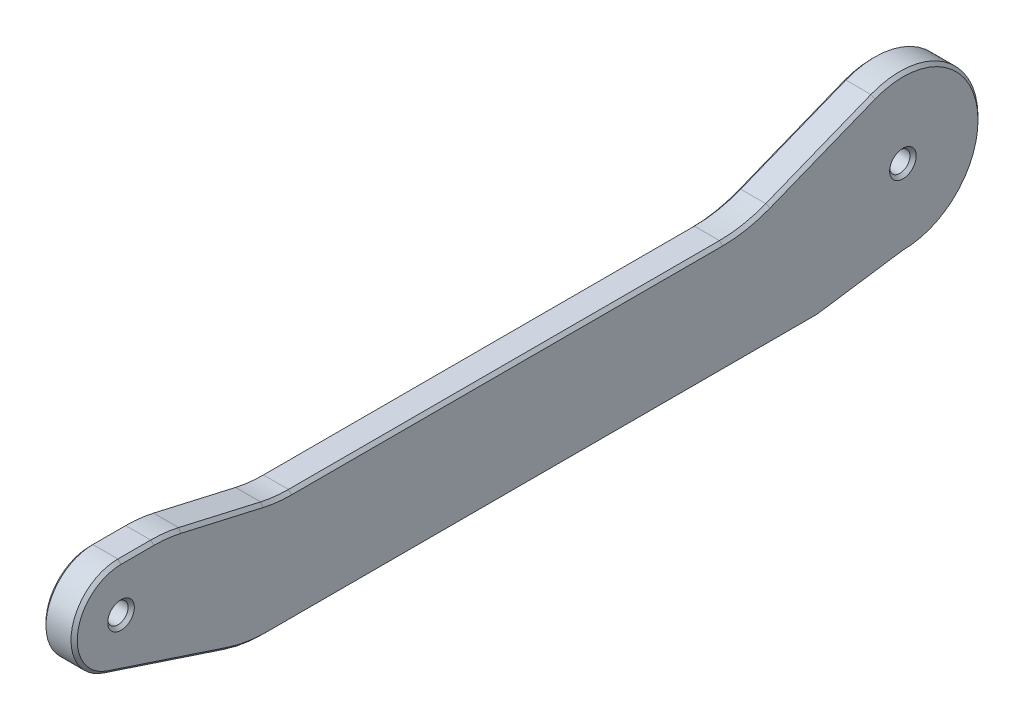
SolidWorks part; units mm, degrees
ref_plane "前视基准面" through (0, 0, 0) normal (0, 0, 1) x (1, 0, 0)
ref_plane "上视基准面" through (0, 0, 0) normal (0, 1, 0) x (1, 0, 0)
ref_plane "右视基准面" through (0, 0, 0) normal (1, 0, 0) x (0, 0, -1)
ref_plane "基准面1" through (2.5, 0, 0) normal (1, 0, 0) x (0, 0, -1)
sketch "草图1" plane through (2.5, 0, 0) normal (1, 0, 0) x (0, 0, -1)
  line L0 (-87.5, -4) -> (-32.5, -4)
  line L1 (-32.5, -7) -> (-87.5, -7)
  line L2 (-28.8354, 3.5) -> (-97.7434, 3.5)
  line L3 (-102.1999, 4.0028) -> (-115.3001, 6.9972)
  line L4 (-119.7566, 7.5) -> (-125, 7.5)
  line L5 (-127.351, -7.122) -> (-108.0536, -13.492)
  line L6 (-101.7844, -14.5) -> (-13.675, -14.5)
  line L7 (-13.675, -14.5) -> (0, -12.5)
  line L8 (-4.6241, 11.6132) -> (-21.4367, 4.9188)
  circle A0 centre (-125, 0) radius 1.625
  circle A1 centre (-97.5, -5.5) radius 1.5
  circle A2 centre (-20, -5.5) radius 1.5
  arc A3 (-87.5, -7) -> (-87.5, -4) centre (-87.5, -5.5) cw
  arc A4 (-32.5, -4) -> (-32.5, -7) centre (-32.5, -5.5) cw
  arc A5 (-97.7434, 3.5) -> (-102.1999, 4.0028) centre (-97.7434, 23.5) cw
  arc A6 (-115.3001, 6.9972) -> (-119.7566, 7.5) centre (-119.7566, -12.5) ccw
  arc A7 (-125, 7.5) -> (-127.351, -7.122) centre (-125, 0) ccw
  arc A8 (-108.0536, -13.492) -> (-101.7844, -14.5) centre (-101.7844, 5.5) ccw
  arc A9 (0, -12.5) -> (-4.6241, 11.6132) centre (0, 0) ccw
  arc A10 (-21.4367, 4.9188) -> (-28.8354, 3.5) centre (-28.8354, 23.5) cw
  circle A11 centre (0, 0) radius 1.625
  dimension "D4" = 1.5
  dimension "D5" = 3
  dimension "D6" = 3.25
  dimension "D7" = 12.5
  dimension "D1" = 3
  dimension "D2" = 68.908
  dimension "D3" = 7.5
  dimension "D8" = 18.0964
extrude "凸台-拉伸1" add sketch "草图1" against normal blind 5
chamfer "倒角1" distance 0.5 angle 45 42 edges at (-2.5, 3.5, 63.2894) (-2.5, 3.6261, 99.9858) (-2.5, 5.5, 108.75) (-2.5, 7.3739, 117.5142) (-2.5, 7.5, 122.3783) (-2.5, 1.1906, 132.4049) (-2.5, -10.307, 117.7023) (-2.5, -14.2464, 104.9592) (-2.5, -14.5, 57.7297) (-2.5, -13.5, 6.8375) (-2.5, 2.3542, -12.2763) (-2.5, 8.266, 13.0304) (-2.5, 3.8579, 25.0686) (-2.5, 0, 126.625) (-2.5, -5.5, 99) (-2.5, -5.5, 21.5) (-2.5, -4, 60) (-2.5, -5.5, 31) (-2.5, -7, 60) (-2.5, -5.5, 89) (-2.5, 0, 1.625) (2.5, 8.266, 13.0304) (2.5, 2.3542, -12.2763) (2.5, -13.5, 6.8375) (2.5, -14.5, 57.7297) (2.5, -14.2464, 104.9592) (2.5, -10.307, 117.7023) (2.5, 1.1906, 132.4049) (2.5, 7.5, 122.3783) (2.5, 7.3739, 117.5142) (2.5, 5.5, 108.75) (2.5, 3.6261, 99.9858) (2.5, 3.5, 63.2894) (2.5, 3.8579, 25.0686) (2.5, 0, 126.625) (2.5, -5.5, 99) (2.5, -5.5, 21.5) (2.5, -5.5, 31) (2.5, -4, 60) (2.5, -5.5, 89) (2.5, -7, 60) (2.5, 0, 1.625)
sketch3d "3D草图1"
  line L0 (2.5, 0.7246, 106.046) -> (2.5, 0.7246, 13.0534)
  line L1 (2.5, 0.7246, 13.0534) -> (2.5, -9.2783, 9.8708)
  line L2 (2.5, -9.2783, 9.8708) -> (2.5, -11.2771, 33.4634)
  line L3 (2.5, -11.2771, 33.4634) -> (2.5, -9.2783, 106.046)
  line L4 (2.5, -9.2783, 106.046) -> (2.5, 0.7246, 106.046)
extrude "凸台-拉伸2" add sketch "3D草图1" along direction (-1, 0, 0) on the side of the normal blind 5
